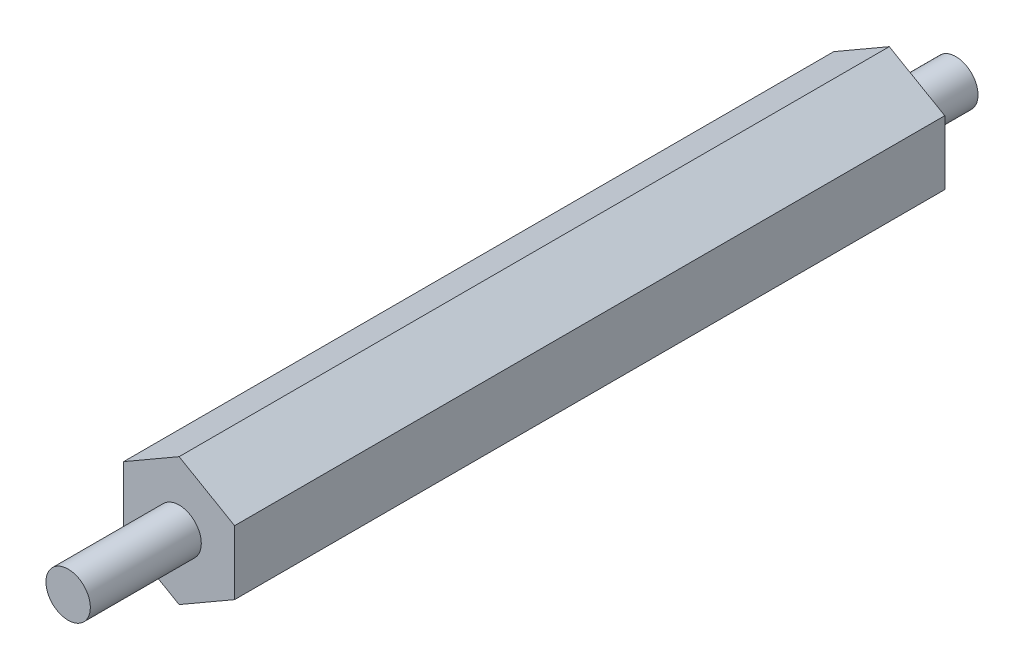
SolidWorks part; units mm, degrees
ref_plane "Piano frontale" through (0, 0, 0) normal (0, 0, 1) x (1, 0, 0)
ref_plane "Piano superiore" through (0, 0, 0) normal (0, 1, 0) x (1, 0, 0)
ref_plane "Piano destro" through (0, 0, 0) normal (1, 0, 0) x (0, 0, -1)
sketch "Schizzo1" plane through (0, 0, 0) normal (0, 0, 1) x (1, 0, 0)
  line L1 (0, -16.9648) -> (-2.5, -18.4081)
  line L2 (-2.5, -18.4081) -> (-2.5, -21.2949)
  line L3 (-2.5, -21.2949) -> (0, -22.7383)
  line L4 (0, -22.7383) -> (2.5, -21.2949)
  line L5 (2.5, -21.2949) -> (2.5, -18.4081)
  line L6 (2.5, -18.4081) -> (0, -16.9648)
  circle A0 centre (0, -19.8515) radius 2.5 construction
  dimension "D1" = 5
extrude "Estrusione-Estrusione1" add sketch "Schizzo1" along normal blind 32
sketch "Schizzo2" plane through (0, 0, 32) normal (0, 0, 1) x (1, 0, 0)
  circle A0 centre (0, -19.8515) radius 1
  dimension "D1" = 2
extrude "Estrusione-Estrusione2" add sketch "Schizzo2" along normal blind 5
sketch "Schizzo4" plane through (0, 0, 0) normal (0, 0, -1) x (-1, 0, 0)
  circle A0 centre (0, -19.8515) radius 1
  dimension "D1" = 2
extrude "Estrusione-Estrusione3" add sketch "Schizzo4" along normal blind 3
